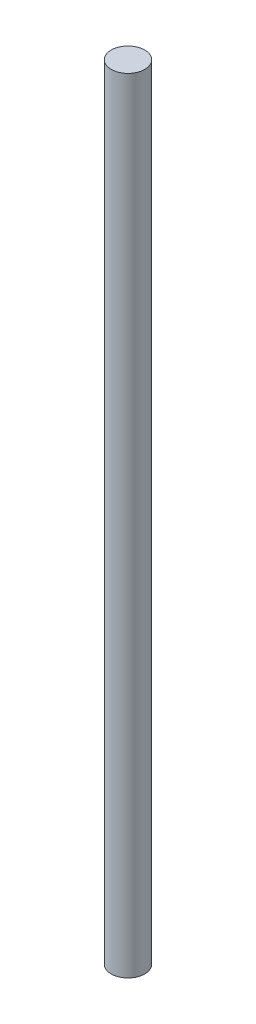
SolidWorks part; units mm, degrees
material "Сталь 20Х13Н4Г9 ГОСТ 5632-72"
ref_plane "Спереди" through (0, 0, 0) normal (0, 0, 1) x (1, 0, 0)
ref_plane "Сверху" through (0, 0, 0) normal (0, 1, 0) x (1, 0, 0)
ref_plane "Справа" through (0, 0, 0) normal (1, 0, 0) x (0, 0, -1)
other "Configuration Table"
sketch "Эскиз1" plane through (0, 0, 0) normal (0, 1, 0) x (1, 0, 0)
  circle A0 centre (0, 0) radius 3
  dimension "D1" = 6
extrude "Бобышка-Вытянуть1" add sketch "Эскиз1" along normal blind 140
